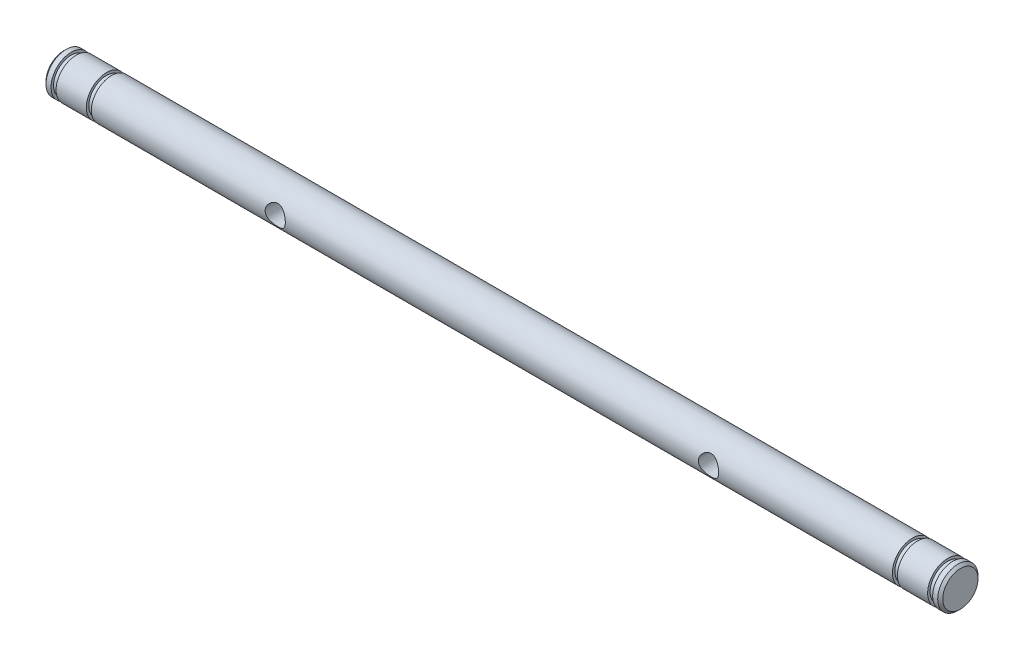
SolidWorks part; units mm, degrees
ref_plane "前视基准面" through (0, 0, 0) normal (0, 0, 1) x (1, 0, 0)
ref_plane "上视基准面" through (0, 0, 0) normal (0, 1, 0) x (1, 0, 0)
ref_plane "右视基准面" through (0, 0, 0) normal (1, 0, 0) x (0, 0, -1)
sketch "草图1" plane through (0, 0, 0) normal (0, 0, 1) x (1, 0, 0)
  line L0 (0, 4) -> (0, 0)
  line L1 (-89, 0) -> (89, 0)
  line L2 (-79.5, 3.5) -> (-79.5, 4)
  line L3 (80.5, 3.5) -> (79.5, 3.5)
  line L4 (80.5, 3.5) -> (80.5, 4)
  line L5 (80.5, 4) -> (86.5, 4)
  line L6 (86.5, 4) -> (86.5, 3.5)
  line L7 (86.5, 3.5) -> (87.5, 3.5)
  line L8 (87.5, 3.5) -> (87.5, 4)
  line L9 (87.5, 4) -> (89, 4)
  line L10 (89, 4) -> (89, 0)
  line L11 (25.5103, 0) -> (135.1344, 0) construction
  line L12 (-89, 4) -> (-89, 0)
  line L13 (79.5, 3.5) -> (79.5, 4)
  line L14 (79.5, 4) -> (-79.5, 4)
  line L15 (-87.5, 4) -> (-89, 4)
  line L16 (-87.5, 3.5) -> (-87.5, 4)
  line L17 (-86.5, 3.5) -> (-87.5, 3.5)
  line L18 (-86.5, 4) -> (-86.5, 3.5)
  line L19 (-80.5, 4) -> (-86.5, 4)
  line L20 (-80.5, 3.5) -> (-80.5, 4)
  line L21 (-80.5, 3.5) -> (-79.5, 3.5)
  dimension "D2" = 79.5
  dimension "D4" = 1
  dimension "D5" = 4
  dimension "D6" = 6
  dimension "D7" = 3.5
  dimension "D8" = 1
  dimension "D9" = 1.5
  dimension "D10" = 4
revolve "旋转1" add sketch "草图1" angle 360 about L11
chamfer "倒角1" distance 0.5 angle 45 2 edges at (89, 0, 4) (-89, 0, 4)
ref_plane "基准面1" through (0, 0, 5) normal (0, 0, 1) x (1, 0, 0)
sketch "草图2" plane through (0, 0, 5) normal (0, 0, 1) x (1, 0, 0)
  line L1 (0, 0) -> (0, 12.0246) construction
  circle A0 centre (43, 0) radius 2
  circle A1 centre (-43, 0) radius 2
  dimension "D3" = 4
  dimension "D1" = 43
extrude "切除-拉伸1" cut sketch "草图2" against normal blind 9
